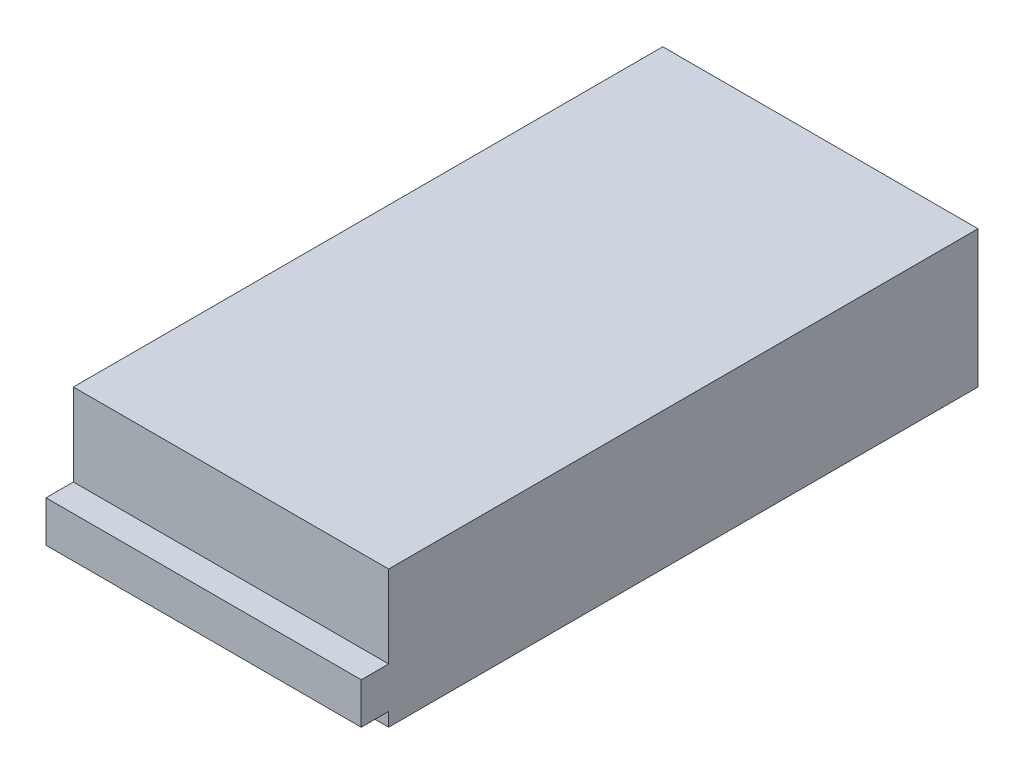
SolidWorks part; units mm, degrees
ref_plane "Front Plane" through (0, 0, 0) normal (0, 0, 1) x (1, 0, 0)
ref_plane "Top Plane" through (0, 0, 0) normal (0, 1, 0) x (1, 0, 0)
ref_plane "Right Plane" through (0, 0, 0) normal (1, 0, 0) x (0, 0, -1)
sketch "Sketch1" plane through (0, 0, 0) normal (0, 1, 0) x (1, 0, 0)
  line L1 (0, 0) -> (115, 0)
  line L2 (0, 0) -> (0, 215)
  line L3 (0, 215) -> (115, 215)
  line L4 (115, 0) -> (115, 215)
  dimension "D1" = 215
  dimension "D2" = 115
extrude "Boss-Extrude1" add sketch "Sketch1" along normal blind 50
sketch "Sketch2" plane through (0, 0, 0) normal (0, 0, 1) x (1, 0, 0)
  line L0 (0, 50) -> (0, 0) construction
  line L1 (0, 5) -> (115, 5)
  line L2 (0, 5) -> (0, 20)
  line L3 (0, 20) -> (115, 20)
  line L4 (115, 5) -> (115, 20)
  line L5 (115, 50) -> (115, 0) construction
  dimension "D1" = 15
  dimension "D2" = 5
extrude "Boss-Extrude2" add sketch "Sketch2" along normal blind 10
